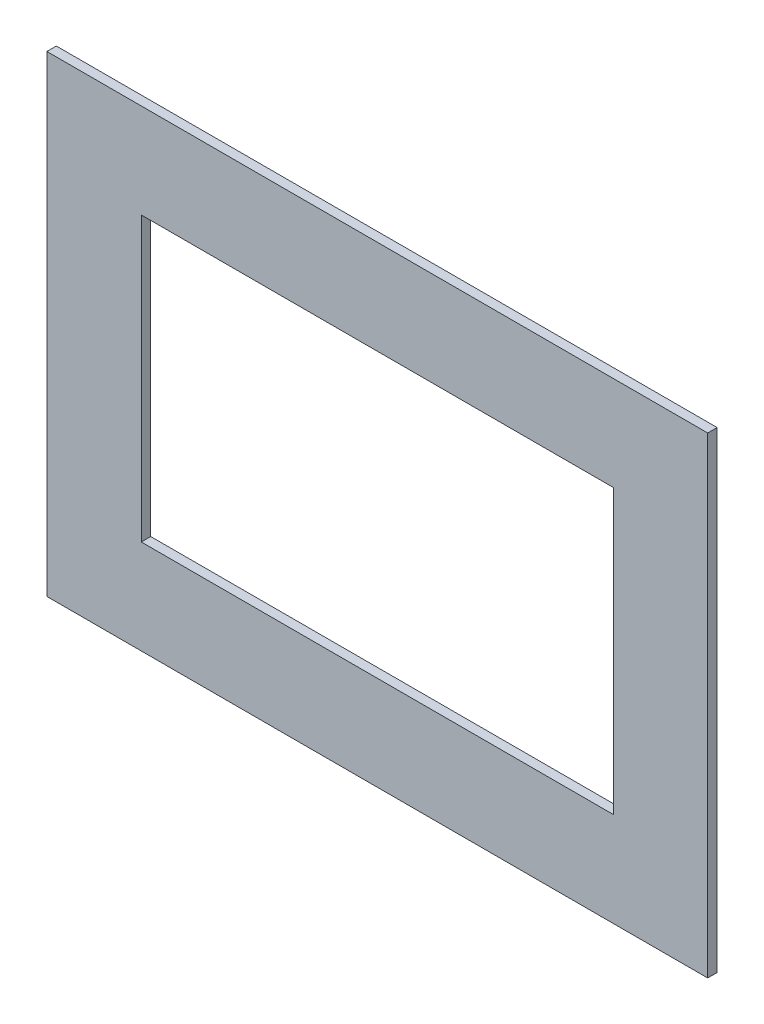
SolidWorks part; units mm, degrees
material "Balsa"
ref_plane "Plan de face" through (0, 0, 0) normal (0, 0, 1) x (1, 0, 0)
ref_plane "Plan de dessus" through (0, 0, 0) normal (0, 1, 0) x (1, 0, 0)
ref_plane "Plan de droite" through (0, 0, 0) normal (1, 0, 0) x (0, 0, -1)
sketch "Esquisse1" plane through (0, 0, 0) normal (0, 0, 1) x (1, 0, 0)
  line L1 (0, 0) -> (-700, 0)
  line L2 (0, 0) -> (0, 500)
  line L3 (0, 500) -> (-700, 500)
  line L4 (-700, 0) -> (-700, 500)
  dimension "D1" = 700
  dimension "D2" = 500
extrude "Boss.-Extru.1" add sketch "Esquisse1" along normal blind 10
sketch "Esquisse2" plane through (0, 0, 0) normal (0, 0, -1) x (-1, 0, 0)
  line L0 (0, 500) -> (700, 500) construction
  line L1 (100, 400) -> (600, 400)
  line L2 (100, 400) -> (100, 100)
  line L3 (100, 100) -> (600, 100)
  line L4 (600, 400) -> (600, 100)
  line L5 (0, 0) -> (0, 500) construction
  line L6 (700, 500) -> (700, 0) construction
  line L7 (700, 0) -> (0, 0) construction
  dimension "D1" = 100
  dimension "D2" = 100
  dimension "D3" = 100
  dimension "D4" = 100
extrude "Enlèv. mat.-Extru.1" cut sketch "Esquisse2" against normal blind 10
